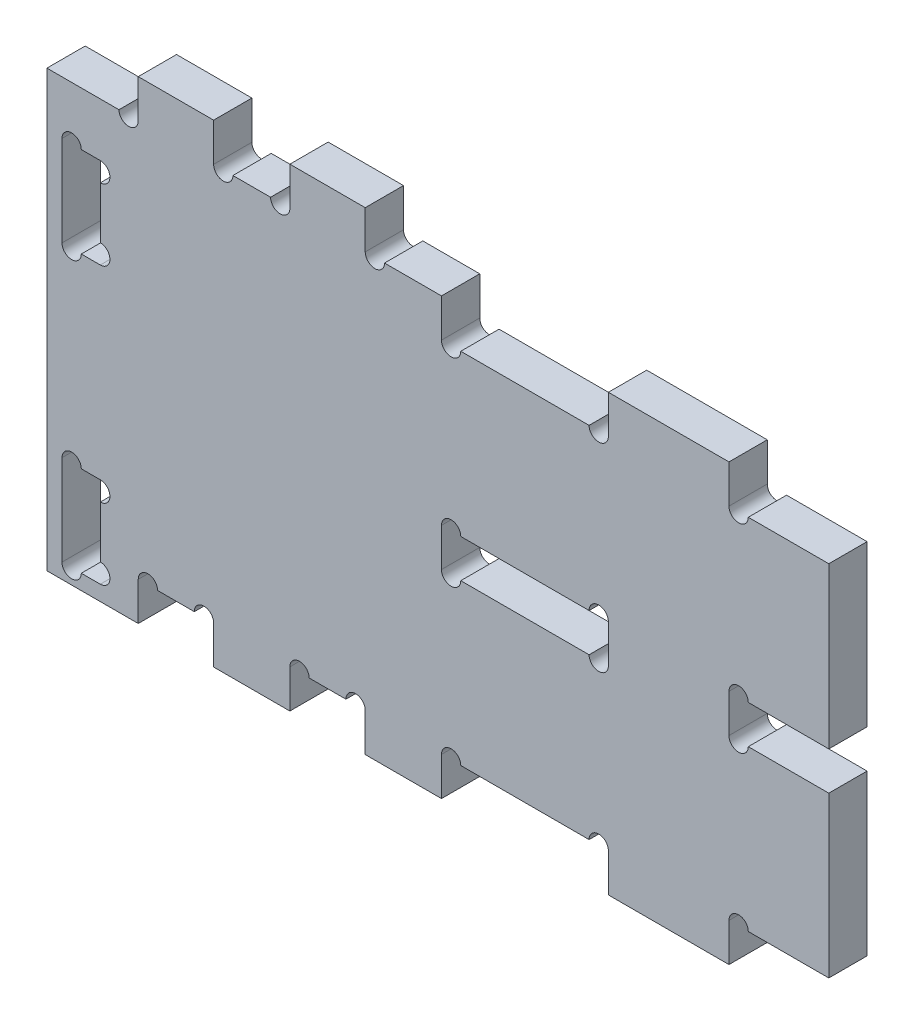
SolidWorks part; units mm, degrees
ref_plane "Front Plane" through (0, 0, 0) normal (0, 0, 1) x (1, 0, 0)
ref_plane "Top Plane" through (0, 0, 0) normal (0, 1, 0) x (1, 0, 0)
ref_plane "Right Plane" through (0, 0, 0) normal (1, 0, 0) x (0, 0, -1)
sketch "Sketch1" plane through (0, 0, 0) normal (0, 0, 1) x (1, 0, 0)
  line L0 (221.23, 144.4) -> (221.23, 131.7)
  line L1 (0, 0) -> (254.34, 0) construction
  line L2 (0, 0) -> (0, 144.4) construction
  line L3 (0, 144.4) -> (254.34, 144.4) construction
  line L4 (254.34, 0) -> (254.34, 144.4) construction
  line L5 (221.23, 131.7) -> (254.34, 131.7)
  line L6 (221.23, 144.4) -> (181.23, 144.4)
  line L7 (181.23, 144.4) -> (181.23, 131.7)
  line L8 (181.23, 131.7) -> (125.87, 131.7)
  line L9 (125.87, 131.7) -> (125.87, 144.4)
  line L10 (125.87, 144.4) -> (0, 144.4) construction
  line L11 (254.34, 131.7) -> (254.34, 78.5)
  line L12 (254.34, 78.5) -> (221.23, 78.5)
  line L13 (221.23, 78.5) -> (221.23, 65.8)
  line L14 (221.23, 65.8) -> (254.34, 65.8)
  line L15 (254.34, 65.8) -> (254.34, 12.7)
  line L16 (254.34, 12.7) -> (221.23, 12.7)
  line L17 (221.23, 12.7) -> (221.23, 0)
  line L18 (221.23, 0) -> (181.23, 0)
  line L19 (254.34, 72.2) -> (0, 72.2) construction
  line L20 (0, 0) -> (-5, 0) construction
  line L21 (125.87, 0) -> (-5, 0)
  line L23 (0, 144.4) -> (-5, 144.4)
  line L24 (-5, 144.4) -> (-5, 0)
  line L26 (221.23, 78.5) -> (181.23, 78.5) construction
  line L27 (0, 126.7) -> (12.7, 126.7)
  line L28 (0, 126.7) -> (0, 96.7)
  line L29 (0, 96.7) -> (12.7, 96.7)
  line L30 (12.7, 126.7) -> (12.7, 96.7)
  line L31 (0, 35) -> (12.7, 35)
  line L32 (0, 35) -> (0, 5)
  line L33 (0, 5) -> (12.7, 5)
  line L34 (12.7, 35) -> (12.7, 5)
  line L35 (181.23, 78.5) -> (181.23, 131.7) construction
  line L36 (221.23, 12.7) -> (181.23, 12.7) construction
  line L37 (181.23, 12.7) -> (181.23, 78.5) construction
  line L38 (0, 144.4) -> (25.29, 144.4)
  line L39 (181.23, 78.5) -> (125.87, 78.5)
  line L40 (181.23, 78.5) -> (181.23, 65.8)
  line L41 (181.23, 65.8) -> (125.87, 65.8)
  line L42 (125.87, 78.5) -> (125.87, 65.8)
  line L43 (181.23, 12.7) -> (125.87, 12.7)
  line L44 (181.23, 12.7) -> (181.23, 0)
  line L46 (125.87, 12.7) -> (125.87, 0)
  line L47 (25.29, 144.4) -> (25.29, 157.1)
  line L48 (25.29, 157.1) -> (50.29, 157.1)
  line L49 (50.29, 157.1) -> (50.29, 144.4)
  line L50 (50.29, 144.4) -> (75.58, 144.4)
  line L51 (75.58, 144.4) -> (75.58, 157.1)
  line L52 (75.58, 157.1) -> (100.58, 157.1)
  line L53 (100.58, 157.1) -> (100.58, 144.4)
  line L54 (100.58, 144.4) -> (125.87, 144.4)
  dimension "D1" = 144.4
  dimension "D2" = 254.34
  dimension "D3" = 128.47
  dimension "D4" = 33.11
  dimension "D5" = 40
  dimension "D6" = 12.7
  dimension "D7" = 65.9
  dimension "D9" = 131.7
  dimension "D10" = 5
  dimension "D11" = 30
  dimension "D12" = 12.7
  dimension "D13" = 5
  dimension "D14" = 5
  dimension "D15" = 12.7
  dimension "D16" = 25
extrude "Boss-Extrude1" add sketch "Sketch1" along normal blind 12.7
sketch "Sketch3" plane through (0, 0, 12.7) normal (0, 0, 1) x (1, 0, 0)
  line L0 (25.29, 157.1) -> (25.29, 0) construction
  line L1 (-5, 0) -> (125.87, 0) construction
  line L2 (50.29, 157.1) -> (50.29, 0) construction
  line L3 (75.58, 157.1) -> (75.58, 0) construction
  line L4 (100.58, 157.1) -> (100.58, 0) construction
  line L6 (50.29, 0) -> (25.29, 0)
  line L7 (50.29, 0) -> (50.29, 12.7)
  line L8 (50.29, 12.7) -> (25.29, 12.7)
  line L9 (25.29, 0) -> (25.29, 12.7)
  line L10 (100.58, 0) -> (75.58, 0)
  line L11 (100.58, 0) -> (100.58, 12.7)
  line L12 (100.58, 12.7) -> (75.58, 12.7)
  line L13 (75.58, 0) -> (75.58, 12.7)
  dimension "D1" = 12.7
extrude "Cut-Extrude2" cut sketch "Sketch3" against normal through all
sketch "Sketch2" plane through (0, 0, 12.7) normal (0, 0, 1) x (1, 0, 0)
  line L0 (181.23, 131.7) -> (125.87, 131.7) construction
  line L2 (254.34, 131.7) -> (221.23, 131.7) construction
  line L3 (221.23, 78.5) -> (254.34, 78.5) construction
  line L4 (254.34, 65.8) -> (221.23, 65.8) construction
  line L5 (221.23, 12.7) -> (254.34, 12.7) construction
  line L8 (181.23, 12.7) -> (125.87, 12.7) construction
  line L9 (125.87, 65.8) -> (181.23, 65.8) construction
  line L10 (181.23, 78.5) -> (125.87, 78.5) construction
  line L11 (12.7, 126.7) -> (0, 126.7) construction
  line L12 (0, 96.7) -> (12.7, 96.7) construction
  line L13 (12.7, 35) -> (0, 35) construction
  line L14 (0, 5) -> (12.7, 5) construction
  line L15 (12.7, 5) -> (12.7, 35) construction
  line L16 (12.7, 96.7) -> (12.7, 126.7) construction
  line L17 (25.29, 144.4) -> (-5, 144.4) construction
  line L18 (75.58, 144.4) -> (50.29, 144.4) construction
  line L19 (125.87, 144.4) -> (100.58, 144.4) construction
  line L20 (50.29, 12.7) -> (25.29, 12.7) construction
  line L21 (100.58, 12.7) -> (75.58, 12.7) construction
  circle A0 centre (129.07, 131.7) radius 3.2
  circle A1 centre (178.03, 131.7) radius 3.2
  circle A2 centre (224.43, 131.7) radius 3.2
  circle A3 centre (224.43, 78.5) radius 3.2
  circle A4 centre (224.43, 65.8) radius 3.2
  circle A5 centre (224.43, 12.7) radius 3.2
  circle A6 centre (28.49, 12.7) radius 3.2
  circle A7 centre (47.09, 12.7) radius 3.2
  circle A8 centre (178.03, 12.7) radius 3.2
  circle A9 centre (178.03, 65.8) radius 3.2
  circle A10 centre (178.03, 78.5) radius 3.2
  circle A11 centre (129.07, 78.5) radius 3.2
  circle A12 centre (129.07, 65.8) radius 3.2
  circle A13 centre (129.07, 12.7) radius 3.2
  circle A14 centre (78.78, 12.7) radius 3.2
  circle A15 centre (3.2, 126.7) radius 3.2
  circle A16 centre (3.2, 96.7) radius 3.2
  circle A17 centre (3.2, 35) radius 3.2
  circle A18 centre (3.2, 5) radius 3.2
  circle A19 centre (12.7, 8.2) radius 3.2
  circle A20 centre (12.7, 31.8) radius 3.2
  circle A21 centre (12.7, 99.9) radius 3.2
  circle A22 centre (12.7, 123.5) radius 3.2
  circle A23 centre (22.09, 144.4) radius 3.2
  circle A24 centre (53.49, 144.4) radius 3.2
  circle A25 centre (72.38, 144.4) radius 3.2
  circle A26 centre (103.78, 144.4) radius 3.2
  circle A27 centre (97.38, 12.7) radius 3.2
  dimension "D1" = 6.4
extrude "Cut-Extrude1" cut sketch "Sketch2" against normal through all
